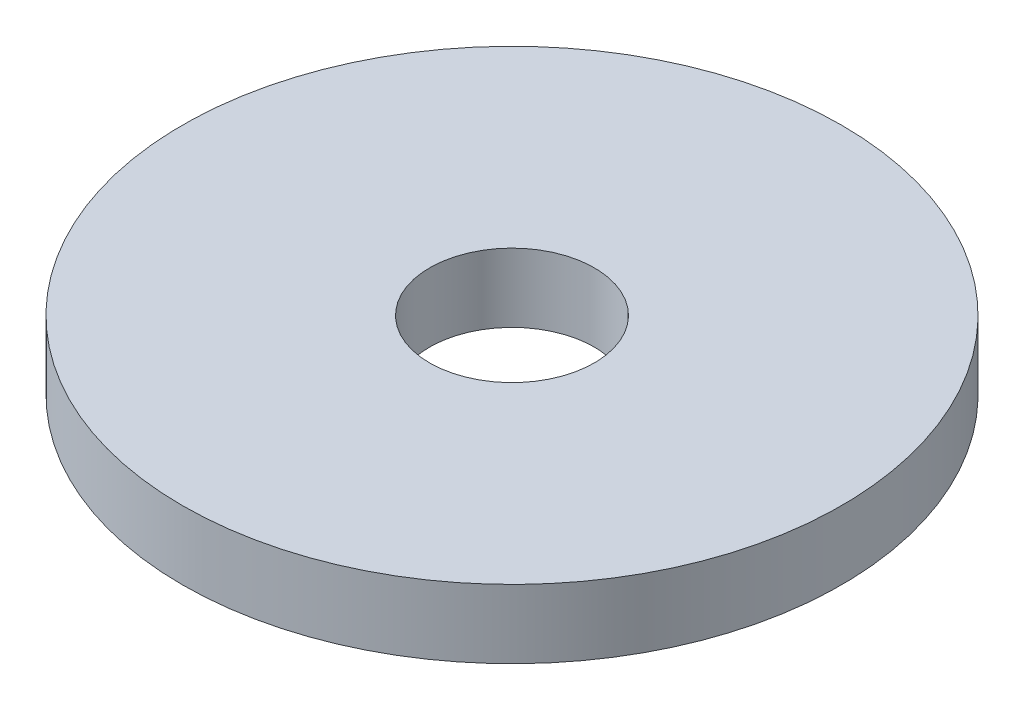
SolidWorks part; units mm, degrees
material "6061-O (SS)"
ref_plane "Płaszczyzna przednia" through (0, 0, 0) normal (0, 0, 1) x (1, 0, 0)
ref_plane "Płaszczyzna górna" through (0, 0, 0) normal (0, 1, 0) x (1, 0, 0)
ref_plane "Płaszczyzna prawa" through (0, 0, 0) normal (1, 0, 0) x (0, 0, -1)
sketch "Szkic1" plane through (0, 0, 0) normal (0, 1, 0) x (1, 0, 0)
  circle A0 centre (0, 0) radius 12
extrude "Dodanie-wyciągnięcie1" add sketch "Szkic1" along normal blind 2.5
sketch "Szkic2" plane through (0, 2.5, 0) normal (0, 1, 0) x (1, 0, 0)
  circle A0 centre (0, 0) radius 3
extrude "Wytnij-wyciągnięcie1" cut sketch "Szkic2" against normal blind 2.5
